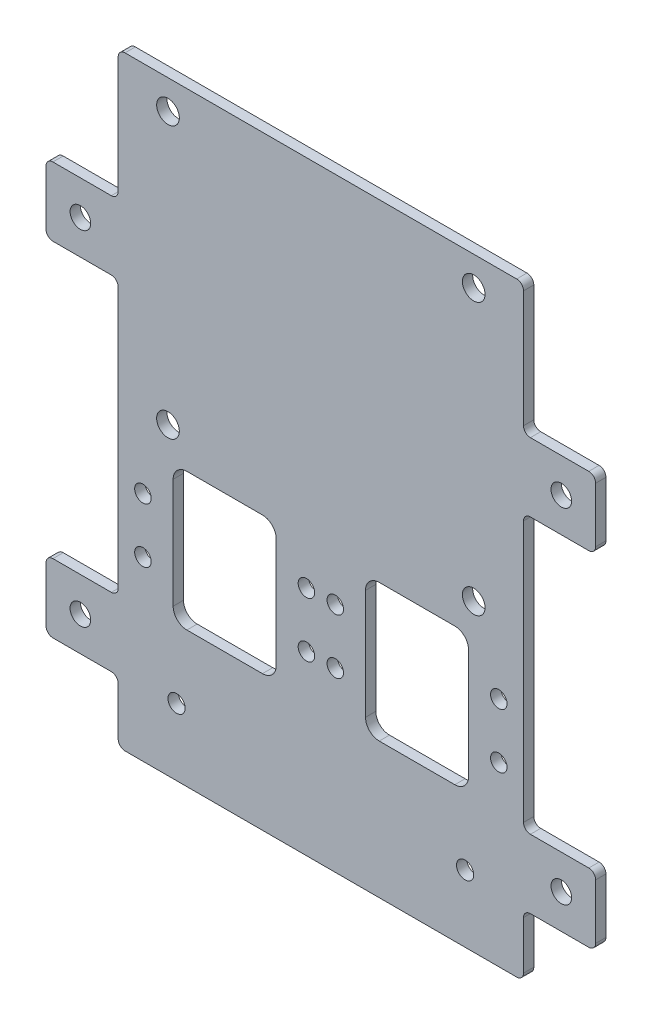
SolidWorks part; units mm, degrees
ref_plane "Спереди" through (0, 0, 0) normal (0, 0, 1) x (1, 0, 0)
ref_plane "Сверху" through (0, 0, 0) normal (0, 1, 0) x (1, 0, 0)
ref_plane "Справа" through (0, 0, 0) normal (1, 0, 0) x (0, 0, -1)
sketch "Model" plane through (0, 0, 0) normal (0, 0, 1) x (1, 0, 0)
  line L0 (-21.5, 37.75) -> (-21.5, 21.75)
  line L1 (-19.5, 19.75) -> (-8.5, 19.75)
  line L2 (-6.5, 21.75) -> (-6.5, 37.75)
  line L3 (-8.5, 39.75) -> (-19.5, 39.75)
  line L4 (19.5, 19.75) -> (8.5, 19.75)
  line L5 (6.5, 21.75) -> (6.5, 37.75)
  line L6 (8.5, 39.75) -> (19.5, 39.75)
  line L7 (19.5, 19.75) -> (8.5, 19.75)
  line L8 (6.5, 21.75) -> (6.5, 37.75)
  line L9 (8.5, 39.75) -> (19.5, 39.75)
  line L10 (-28.5, 0) -> (28.5, 0)
  line L11 (28.5, 88) -> (-28.5, 88)
  line L12 (-39, 69) -> (-30.5, 69)
  line L13 (-39, 59) -> (-30.5, 59)
  line L14 (-40, 64) -> (-40, 68)
  line L15 (-40, 64) -> (-40, 60)
  line L16 (-38, 9) -> (-31.5, 9)
  line L17 (-38, 19) -> (-31.5, 19)
  line L18 (-40, 14) -> (-40, 11)
  line L19 (-40, 14) -> (-40, 17)
  line L20 (-39, 9) -> (-30.5, 9)
  line L21 (-39, 19) -> (-30.5, 19)
  line L22 (-40, 14) -> (-40, 10)
  line L23 (-40, 14) -> (-40, 18)
  line L24 (-29.5, 8) -> (-29.5, 1)
  line L25 (21.5, 37.75) -> (21.5, 21.75)
  line L26 (38, 69) -> (31.5, 69)
  line L27 (38, 59) -> (31.5, 59)
  line L28 (40, 64) -> (40, 67)
  line L29 (40, 64) -> (40, 61)
  line L30 (38, 9) -> (31.5, 9)
  line L31 (38, 19) -> (31.5, 19)
  line L32 (40, 14) -> (40, 11)
  line L33 (40, 14) -> (40, 17)
  line L34 (38, 9) -> (31.5, 9)
  line L35 (38, 19) -> (31.5, 19)
  line L36 (40, 14) -> (40, 11)
  line L37 (40, 14) -> (40, 17)
  line L38 (29.5, 87) -> (29.5, 70)
  line L39 (21.5, 37.75) -> (21.5, 21.75)
  line L40 (39, 69) -> (30.5, 69)
  line L41 (39, 59) -> (30.5, 59)
  line L42 (40, 64) -> (40, 68)
  line L43 (40, 64) -> (40, 60)
  line L44 (38, 9) -> (31.5, 9)
  line L45 (38, 19) -> (31.5, 19)
  line L46 (40, 14) -> (40, 11)
  line L47 (40, 14) -> (40, 17)
  line L48 (39, 9) -> (30.5, 9)
  line L49 (39, 19) -> (30.5, 19)
  line L50 (40, 14) -> (40, 10)
  line L51 (40, 14) -> (40, 18)
  line L52 (29.5, 8) -> (29.5, 1)
  line L53 (-29.5, 87) -> (-29.5, 70)
  line L54 (-29.5, 20) -> (-29.5, 58)
  line L55 (29.5, 58) -> (29.5, 20)
  arc A0 (-19.5, 39.75) -> (-21.5, 37.75) centre (-19.5, 37.75) ccw
  arc A1 (-6.5, 37.75) -> (-8.5, 39.75) centre (-8.5, 37.75) ccw
  arc A2 (-21.5, 21.75) -> (-19.5, 19.75) centre (-19.5, 21.75) ccw
  arc A3 (-8.5, 19.75) -> (-6.5, 21.75) centre (-8.5, 21.75) ccw
  arc A4 (8.5, 39.75) -> (6.5, 37.75) centre (8.5, 37.75) ccw
  arc A5 (6.5, 21.75) -> (8.5, 19.75) centre (8.5, 21.75) ccw
  arc A6 (8.5, 39.75) -> (6.5, 37.75) centre (8.5, 37.75) ccw
  arc A7 (6.5, 21.75) -> (8.5, 19.75) centre (8.5, 21.75) ccw
  circle A8 centre (-21, 9.75) radius 1.25
  circle A9 centre (-22.25, 83.75) radius 1.65
  circle A10 centre (-22.25, 44.25) radius 1.65
  circle A11 centre (-25.9, 33.75) radius 1.2
  circle A12 centre (-25.9, 25.75) radius 1.2
  circle A13 centre (-2.1, 33.75) radius 1.2
  circle A14 centre (-2.1, 25.75) radius 1.2
  circle A15 centre (2.1, 33.75) radius 1.2
  circle A16 centre (2.1, 25.75) radius 1.2
  circle A17 centre (-35, 64) radius 1.5
  circle A18 centre (-35, 14) radius 1.5
  circle A19 centre (-35, 14) radius 1.5
  arc A20 (21.5, 37.75) -> (19.5, 39.75) centre (19.5, 37.75) ccw
  arc A21 (19.5, 19.75) -> (21.5, 21.75) centre (19.5, 21.75) ccw
  circle A22 centre (21, 9.75) radius 1.25
  circle A23 centre (22.25, 83.75) radius 1.65
  circle A24 centre (22.25, 44.25) radius 1.65
  circle A25 centre (25.9, 33.75) radius 1.2
  circle A26 centre (25.9, 25.75) radius 1.2
  circle A27 centre (35, 64) radius 1.5
  circle A28 centre (35, 14) radius 1.5
  circle A29 centre (35, 14) radius 1.5
  arc A30 (21.5, 37.75) -> (19.5, 39.75) centre (19.5, 37.75) ccw
  arc A31 (19.5, 19.75) -> (21.5, 21.75) centre (19.5, 21.75) ccw
  circle A32 centre (21, 9.75) radius 1.25
  circle A33 centre (22.25, 83.75) radius 1.65
  circle A34 centre (22.25, 44.25) radius 1.65
  circle A35 centre (25.9, 33.75) radius 1.2
  circle A36 centre (25.9, 25.75) radius 1.2
  circle A37 centre (35, 64) radius 1.5
  circle A38 centre (35, 14) radius 1.5
  circle A39 centre (35, 14) radius 1.5
  arc A40 (-29.5, 1) -> (-28.5, 0) centre (-28.5, 1) ccw
  arc A41 (28.5, 0) -> (29.5, 1) centre (28.5, 1) ccw
  arc A42 (-28.5, 88) -> (-29.5, 87) centre (-28.5, 87) ccw
  arc A43 (29.5, 87) -> (28.5, 88) centre (28.5, 87) ccw
  arc A44 (40, 68) -> (39, 69) centre (39, 68) ccw
  arc A45 (39, 59) -> (40, 60) centre (39, 60) ccw
  arc A46 (40, 18) -> (39, 19) centre (39, 18) ccw
  arc A47 (39, 9) -> (40, 10) centre (39, 10) ccw
  arc A48 (-40, 10) -> (-39, 9) centre (-39, 10) ccw
  arc A49 (-39, 19) -> (-40, 18) centre (-39, 18) ccw
  arc A50 (-40, 60) -> (-39, 59) centre (-39, 60) ccw
  arc A51 (-39, 69) -> (-40, 68) centre (-39, 68) ccw
  arc A52 (-30.5, 69) -> (-29.5, 70) centre (-30.5, 70) ccw
  arc A53 (29.5, 70) -> (30.5, 69) centre (30.5, 70) ccw
  arc A54 (-29.5, 58) -> (-30.5, 59) centre (-30.5, 58) ccw
  arc A55 (30.5, 59) -> (29.5, 58) centre (30.5, 58) ccw
  arc A56 (-30.5, 19) -> (-29.5, 20) centre (-30.5, 20) ccw
  arc A57 (29.5, 20) -> (30.5, 19) centre (30.5, 20) ccw
  arc A58 (-29.5, 8) -> (-30.5, 9) centre (-30.5, 8) ccw
  arc A59 (30.5, 9) -> (29.5, 8) centre (30.5, 8) ccw
extrude "Бобышка-Вытянуть1" add sketch "Model" along normal blind 1.5 contours A59 L48 L30 A47 L50 L32 L33 L51 A46 L49 L31 A57 L55 A55 L41 L27 A45 L43 L29 L28 L42 A44 L40 L26 A53 L38 A43 L11 A42 L53 A52 L12 A51 L14 L15 A50 L13 A54 L54 A56 L21 L17 A49 L23 L19 L18
